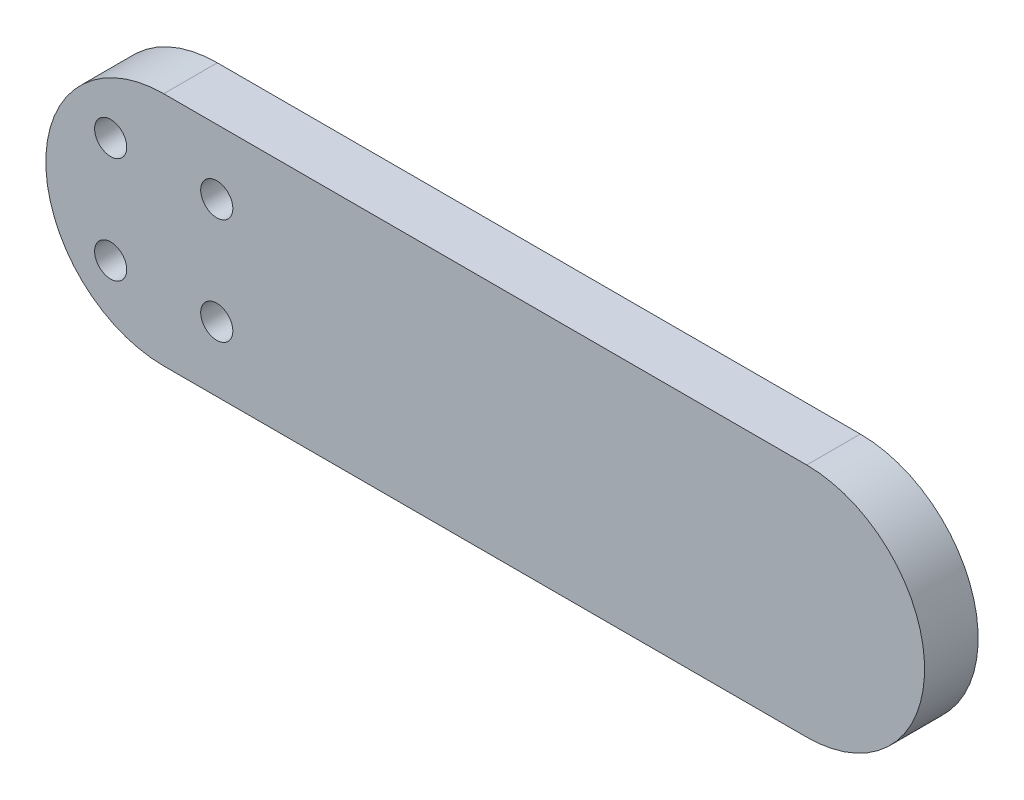
SolidWorks part; units mm, degrees
ref_plane "Front Plane" through (0, 0, 0) normal (0, 0, 1) x (1, 0, 0)
ref_plane "Top Plane" through (0, 0, 0) normal (0, 1, 0) x (1, 0, 0)
ref_plane "Right Plane" through (0, 0, 0) normal (1, 0, 0) x (0, 0, -1)
sketch "Sketch1" plane through (0, 0, 0) normal (0, 0, 1) x (1, 0, 0)
  line L0 (0, 15) -> (0, 20) construction
  line L1 (0, 0) -> (60, 0) construction
  line L2 (0, 11) -> (60, 11)
  line L3 (0, -11) -> (60, -11)
  line L4 (0, 0) -> (0, 11) construction
  line L5 (0, 0) -> (-4.9497, 4.9497) construction
  arc A0 (0, 11) -> (0, -11) centre (0, 0) ccw
  arc A10 (60, -11) -> (60, 11) centre (60, 0) ccw
  circle A11 centre (-4.9497, 4.9497) radius 1.5
  circle A12 centre (4.9497, 4.9497) radius 1.5
  circle A13 centre (4.9497, -4.9497) radius 1.5
  circle A14 centre (-4.9497, -4.9497) radius 1.5
  point P16 (0, 0)
  point P23 (0, 0)
  dimension "D1" = 22
  dimension "D2" = 7
  dimension "D4" = 45
  dimension "D7" = 22
  dimension "D5" = 3
  dimension "D3" = 5
  dimension "D6" = 60
  dimension "D8" = 4
extrude "Boss-Extrude2" add sketch "Sketch1" along normal blind 5
